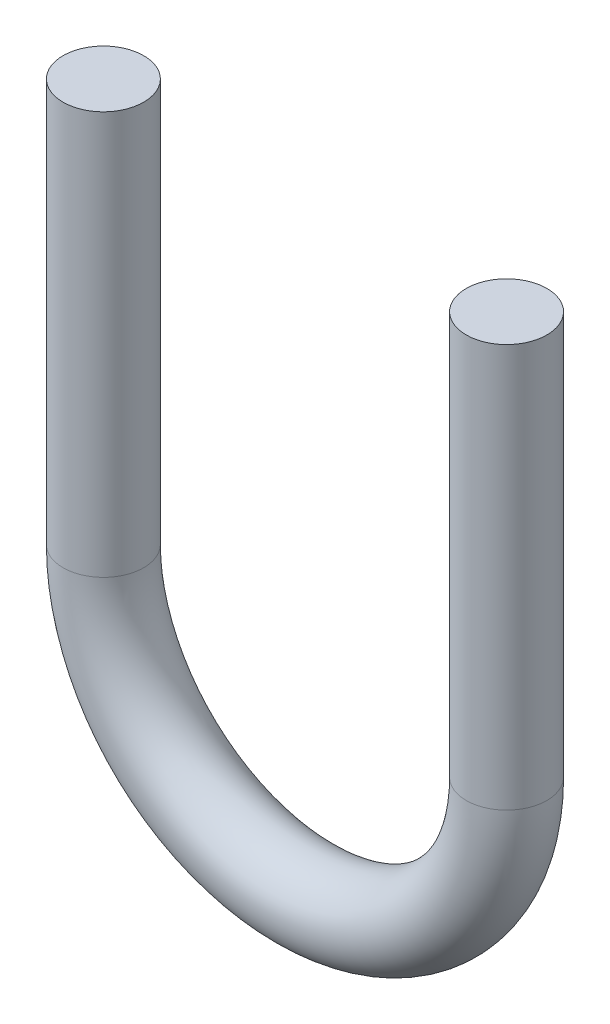
SolidWorks part; units mm, degrees
ref_plane "Front Plane" through (0, 0, 0) normal (0, 0, 1) x (1, 0, 0)
ref_plane "Top Plane" through (0, 0, 0) normal (0, 1, 0) x (1, 0, 0)
ref_plane "Right Plane" through (0, 0, 0) normal (1, 0, 0) x (0, 0, -1)
sketch "Sketch1" plane through (0, 0, 0) normal (0, 0, 1) x (1, 0, 0)
  line L0 (-12.7, 0) -> (-12.7, 31.75)
  line L1 (12.7, 0) -> (12.7, 31.75)
  arc A0 (-12.7, 0) -> (12.7, 0) centre (0, 0) ccw
  dimension "D1" = 12.7
  dimension "D2" = 44.45
ref_plane "Plane1" through (0, 31.75, 0) normal (0, 1, 0) x (1, 0, 0)
sketch "Sketch2" plane through (0, 31.75, 0) normal (0, 1, 0) x (1, 0, 0)
  circle A0 centre (-15.875, 0) radius 3.175
  dimension "D1" = 6.35
sweep "Sweep1" add profiles "Sketch2" path "Sketch1"
